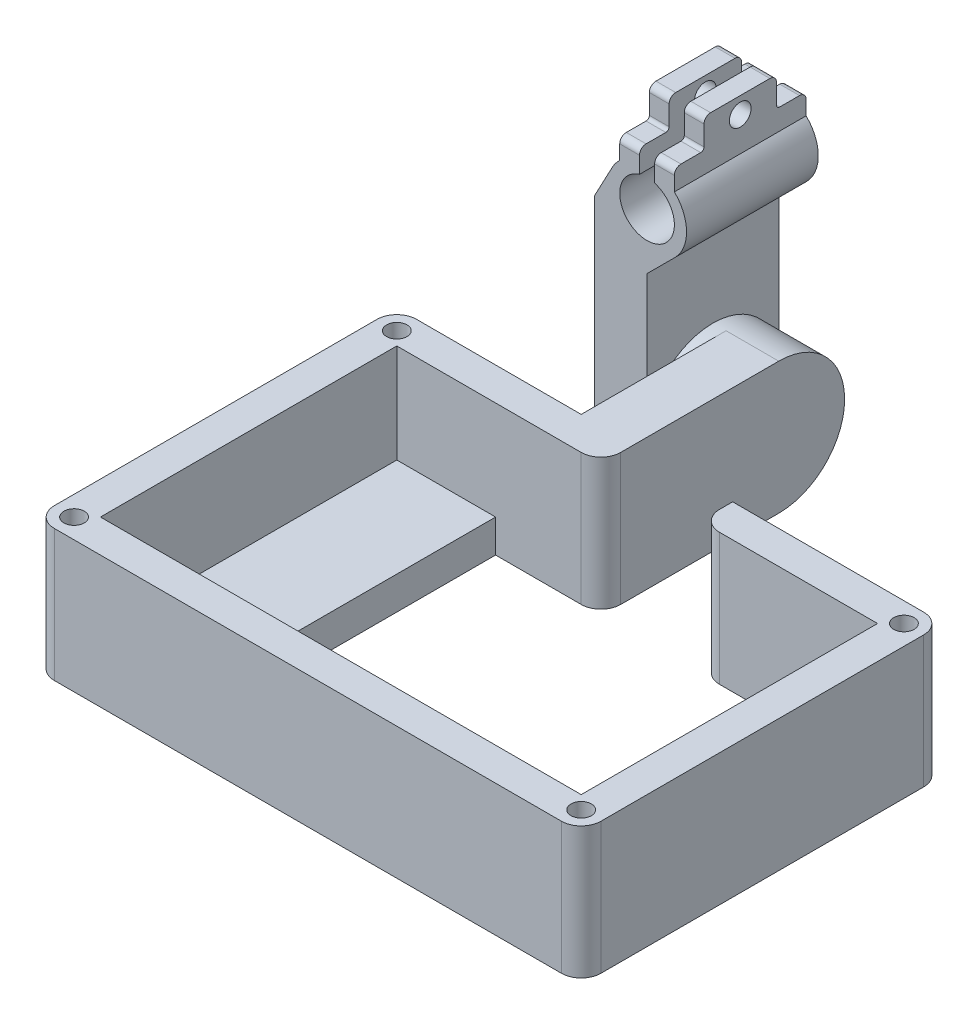
SolidWorks part; units mm, degrees
ref_plane "前视基准面" through (0, 0, 0) normal (0, 0, 1) x (1, 0, 0)
ref_plane "上视基准面" through (0, 0, 0) normal (0, 1, 0) x (1, 0, 0)
ref_plane "右视基准面" through (0, 0, 0) normal (1, 0, 0) x (0, 0, -1)
other "Configuration Table"
sketch "草图1" plane through (0, 0, 0) normal (0, 0, 1) x (1, 0, 0)
  line L0 (-1.15, 3.9875) -> (-1.15, 12)
  line L1 (0, 0) -> (0, 9.969) construction
  line L2 (-1.15, 12) -> (-4.15, 12)
  line L3 (-4.15, 12) -> (-4.15, 4.3333)
  line L4 (4.15, 12) -> (4.15, 4.3333)
  line L5 (1.15, 12) -> (4.15, 12)
  line L6 (1.15, 3.9875) -> (1.15, 12)
  line L7 (-8, -2.2655) -> (-5.2977, 2.8168)
  line L8 (-8, -2.2655) -> (-8, -30)
  line L9 (4.2426, -4.2426) -> (0, -8.4853)
  line L10 (0, -8.4853) -> (0, -30)
  line L11 (-8, -30) -> (0, -30)
  arc A0 (-1.15, 3.9875) -> (1.15, 3.9875) centre (0, 0) ccw
  arc A1 (-4.15, 4.3333) -> (-5.2977, 2.8168) centre (0, 0) ccw
  arc A2 (4.2426, -4.2426) -> (4.15, 4.3333) centre (0, 0) ccw
  dimension "D1" = 8.3
  dimension "D4" = 12
  dimension "D2" = 2.3
  dimension "D3" = 12
  dimension "D5" = 3
  dimension "D6" = 30
  dimension "D7" = 152
  dimension "D8" = 8
  dimension "D9" = 135
extrude "凸台-拉伸1" add sketch "草图1" along normal mid plane 20
sketch "草图2" plane through (0, 0, 0) normal (1, 0, 0) x (0, 0, -1)
  line L0 (-10, -30) -> (10, -30) construction
  circle A0 centre (0, -30) radius 10
extrude "凸台-拉伸2" add sketch "草图2" against normal up to surface and the other way blind 2 up to face at (-8, -16.1327, 0)
sketch "草图6" plane through (4.15, 0, 0) normal (1, 0, 0) x (0, 0, -1)
  line L0 (0, 0) -> (0, 16.5087) construction
  line L1 (-10, 12) -> (10, 12) construction
  line L2 (-5.5, 7.5) -> (-20.2045, 7.5)
  line L3 (-5.5, 7.5) -> (-5.5, 16.0204)
  line L4 (-5.5, 16.0204) -> (-20.2045, 16.0204)
  line L5 (-20.2045, 7.5) -> (-20.2045, 16.0204)
  line L6 (20.2045, 7.5) -> (20.2045, 16.0204)
  line L7 (5.5, 16.0204) -> (20.2045, 16.0204)
  line L8 (5.5, 7.5) -> (5.5, 16.0204)
  line L9 (5.5, 7.5) -> (20.2045, 7.5)
  circle A0 centre (0, 9.5) radius 1.65
  dimension "D3" = 3.3
  dimension "D1" = 11
  dimension "D2" = 4.5
  dimension "D4" = 2.5
extrude "切除-拉伸2" cut sketch "草图6" against normal through all
fillet "圆角1" radius 1 8 edges at (2.65, 7.5, -10) (-2.65, 7.5, -10) (-2.65, 7.5, 10) (2.65, 7.5, 10) (-2.65, 12, 5.5) (2.65, 12, -5.5) (-2.65, 12, -5.5) (2.65, 12, 5.5)
fillet "圆角2" radius 0.5 4 edges at (2.65, 7.5, -5.5) (-2.65, 7.5, -5.5) (2.65, 7.5, 5.5) (-2.65, 7.5, 5.5)
sketch "草图7" plane through (2, 0, 0) normal (1, 0, 0) x (0, 0, -1)
  line L0 (0, -20) -> (-22, -20)
  line L1 (0, -40) -> (-22, -40)
  line L2 (-22, -20) -> (-22, -40)
  arc A0 (0, -20) -> (0, -40) centre (0, -30) cw
  arc A1 (10, -30) -> (-10, -30) centre (0, -30) ccw construction
  dimension "D1" = 22
  dimension "D2" = 22
extrude "凸台-拉伸3" add sketch "草图7" along normal blind 8
sketch "草图8" plane through (0, 0, 22) normal (0, 0, 1) x (1, 0, 0)
  line L0 (2, -27) -> (2, -49.77) construction
  line L1 (10, -20) -> (-26, -20)
  line L2 (-26, -20) -> (-26, -40)
  line L3 (-26, -40) -> (2, -40)
  line L4 (10, -20) -> (57, -20)
  line L5 (2, -40) -> (57, -40)
  line L6 (57, -20) -> (57, -40)
  dimension "D1" = 36
  dimension "D2" = 20
  dimension "D3" = 47
extrude "凸台-拉伸4" add sketch "草图8" along normal blind 55
sketch "草图9" plane through (0, -20, 0) normal (0, 1, 0) x (1, 0, 0)
  line L0 (57, -22) -> (10, -22) construction
  line L1 (-21, -27) -> (52, -27)
  line L2 (-21, -27) -> (-21, -72)
  line L3 (-21, -72) -> (52, -72)
  line L4 (52, -27) -> (52, -72)
  line L5 (57, -77) -> (57, -22) construction
  line L6 (-26, -77) -> (-26, -22) construction
  line L7 (57, -77) -> (-26, -77) construction
  dimension "D1" = 5
  dimension "D2" = 5
  dimension "D3" = 5
  dimension "D4" = 5
extrude "切除-拉伸3" cut sketch "草图9" against normal blind 13
sketch "草图10" plane through (0, 0, 22) normal (0, 0, -1) x (-1, 0, 0)
  line L0 (-10, -40) -> (-57, -40) construction
  line L1 (-10, -20) -> (-25, -20)
  line L2 (-10, -20) -> (-10, -40)
  line L3 (-10, -40) -> (-25, -40)
  line L4 (-25, -20) -> (-25, -40)
  dimension "D1" = 15
extrude "切除-拉伸4" cut sketch "草图10" against normal blind 13
sketch "草图11" plane through (0, -33, 0) normal (0, 1, 0) x (1, 0, 0)
  line L1 (-21, -72) -> (52, -72)
  line L2 (-21, -72) -> (-21, -27)
  line L3 (-21, -27) -> (52, -27)
  line L4 (52, -72) -> (52, -27)
extrude "切除-拉伸6" cut sketch "草图11" against normal blind 13
sketch "草图12" plane through (0, -40, 0) normal (0, -1, 0) x (1, 0, 0)
  line L0 (-21, 72) -> (52, 72) construction
  line L1 (-21, 27) -> (-6, 27)
  line L2 (-21, 27) -> (-21, 72)
  line L3 (-21, 72) -> (-6, 72)
  line L4 (-6, 27) -> (-6, 72)
  line L6 (52, 27) -> (42, 27)
  line L7 (52, 27) -> (52, 72)
  line L8 (52, 72) -> (42, 72)
  line L9 (42, 27) -> (42, 72)
  dimension "D1" = 10
  dimension "D2" = 15
extrude "凸台-拉伸5" add sketch "草图12" against normal blind 5
fillet "圆角3" radius 3 6 edges at (-26, -30, 77) (-26, -30, 22) (57, -30, 22) (57, -30, 77) (25, -30, 27) (10, -30, 27)
sketch "草图14" plane through (0, -20, 0) normal (0, 1, 0) x (1, 0, 0)
  circle A0 centre (-23, -25) radius 1.55
  circle A1 centre (54, -25) radius 1.55
  circle A2 centre (-23, -74) radius 1.55
  circle A3 centre (54, -74) radius 1.55
  dimension "D1" = 3.1
  dimension "D2" = 3.1
  dimension "D3" = 3.1
  dimension "D4" = 3.1
  dimension "D5" = 49
  dimension "D6" = 77
extrude "切除-拉伸7" cut sketch "草图14" against normal through all
